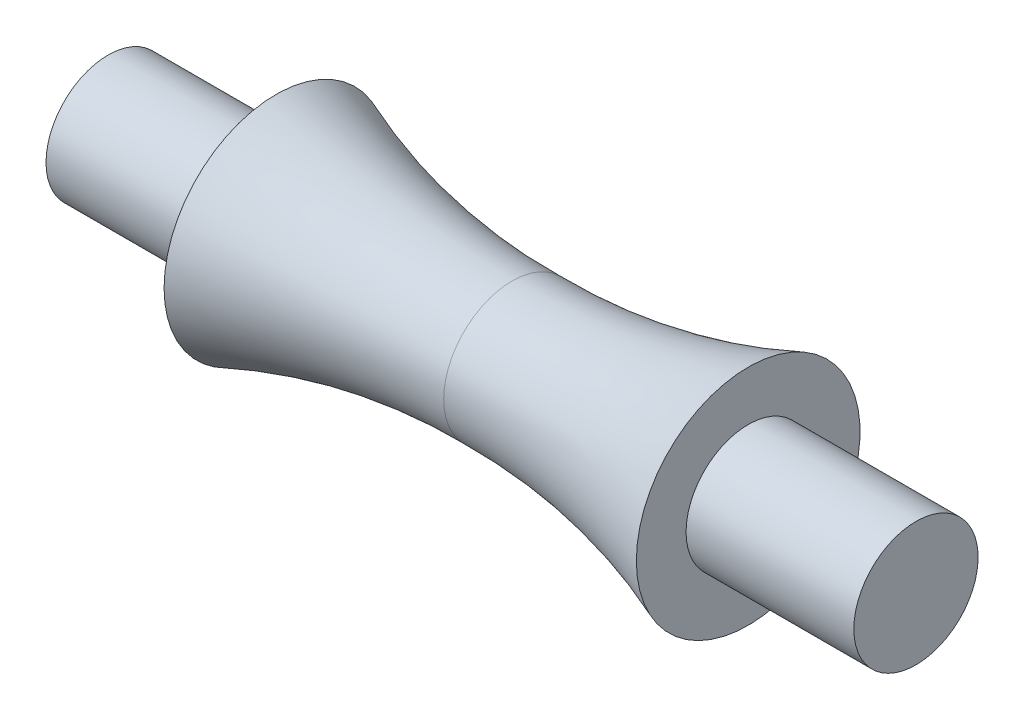
SolidWorks part; units mm, degrees
material "Polyethylene Cross-Linked"
ref_plane "Front Plane" through (0, 0, 0) normal (0, 0, 1) x (1, 0, 0)
ref_plane "Top Plane" through (0, 0, 0) normal (0, 1, 0) x (1, 0, 0)
ref_plane "Right Plane" through (0, 0, 0) normal (1, 0, 0) x (0, 0, -1)
sketch "Sketch1" plane through (0, 0, 0) normal (0, 1, 0) x (1, 0, 0)
  line L0 (0, 0) -> (8.255, 0)
  line L1 (8.255, 0) -> (8.255, 1.27)
  line L2 (8.255, 1.27) -> (4.826, 1.27)
  line L3 (4.826, 1.27) -> (4.826, 2.286)
  line L4 (0, 0) -> (0, 1.397)
  arc A0 (0, 1.397) -> (4.826, 2.286) centre (0.1556, 14.096) ccw
  dimension "D6" = 12.7
  dimension "D1" = 1.27
  dimension "D2" = 2.286
  dimension "D3" = 1.397
  dimension "D4" = 8.255
  dimension "D5" = 4.826
sketch "Sketch2" plane through (0, 0, 0) normal (0, 0, 1) x (1, 0, 0)
  line L0 (0, 0) -> (8.255, 0)
revolve "Revolve1" add sketch "Sketch1" angle 360 about L0
mirror "Mirror1" about plane through (0, 0, 0) normal (1, 0, 0) of "Revolve1"
